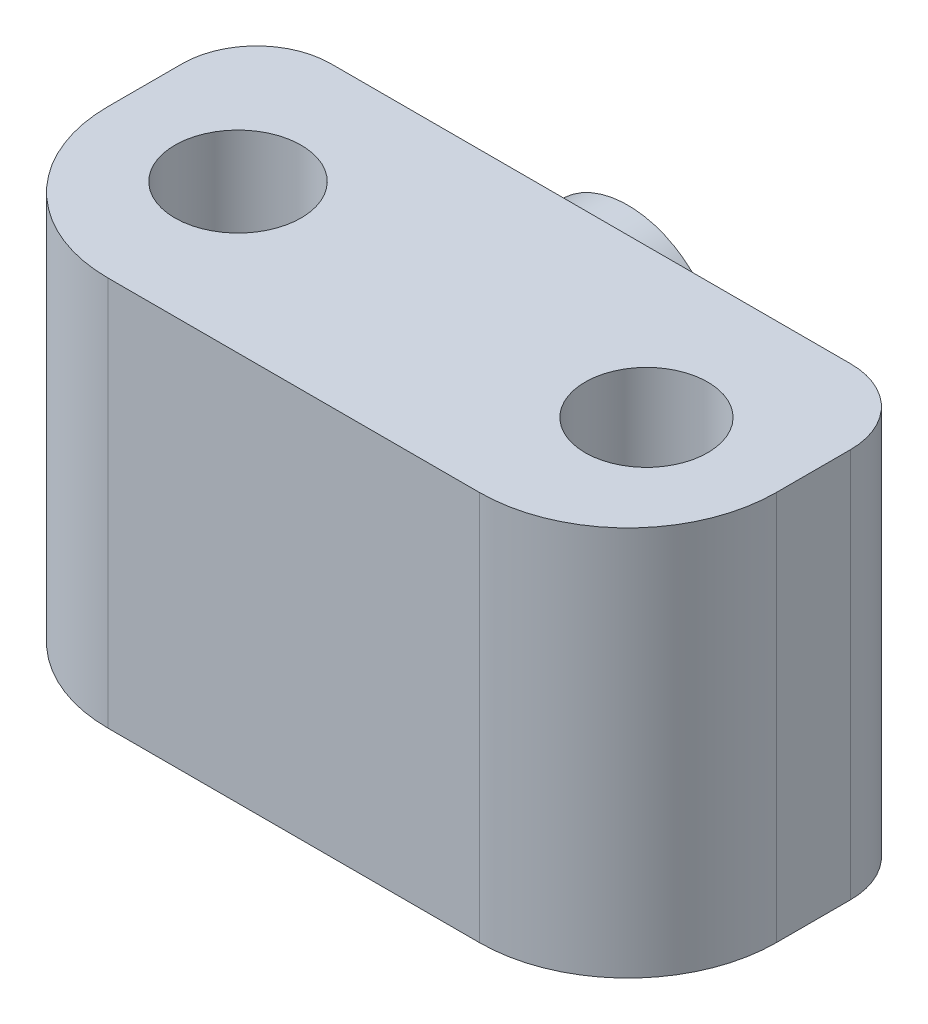
SolidWorks part; units mm, degrees
ref_plane "前视基准面" through (0, 0, 0) normal (0, 0, 1) x (1, 0, 0)
ref_plane "上视基准面" through (0, 0, 0) normal (0, 1, 0) x (1, 0, 0)
ref_plane "右视基准面" through (0, 0, 0) normal (1, 0, 0) x (0, 0, -1)
sketch "草图1" plane through (0, 0, 0) normal (0, 0, 1) x (1, 0, 0)
  line L1 (-9, 6.25) -> (9, 6.25)
  line L2 (-9, 6.25) -> (-9, -6.25)
  line L3 (-9, -6.25) -> (9, -6.25)
  line L4 (9, 6.25) -> (9, -6.25)
  line L5 (-9, 6.25) -> (9, -6.25) construction
  line L6 (-9, -6.25) -> (9, 6.25) construction
  point P0 (0, 0)
  dimension "D2" = 18
  dimension "D3" = 12.5
extrude "凸台-拉伸1" add sketch "草图1" along normal blind 8
sketch "草图2" plane through (0, 0, 0) normal (0, 0, -1) x (-1, 0, 0)
  line L0 (0, 1.45) -> (0, 0) construction
  circle A1 centre (0, 1.45) radius 1.625
  dimension "D1" = 1.45
  dimension "D2" = 3.25
extrude "切除-拉伸1" cut sketch "草图2" against normal mid plane 5
sketch "草图3" plane through (0, 0, 0) normal (0, 0, -1) x (-1, 0, 0)
  circle A3 centre (0, 1.45) radius 2.5
  circle A4 centre (0, 1.45) radius 1.625
  dimension "D1" = 3.25
  dimension "D2" = 5
extrude "凸台-拉伸2" add sketch "草图3" along normal blind 1
sketch "草图4" plane through (0, 6.25, 0) normal (0, 1, 0) x (1, 0, 0)
  line L0 (-9, -4) -> (9, -4) construction
  line L1 (-9, -8) -> (-9, 0) construction
  line L2 (9, -8) -> (9, 0) construction
  circle A0 centre (-5.5, -4) radius 1.25
  point P6 (-5.5, -4)
  dimension "D2" = 2.5
  dimension "D1" = 3.5
extrude "切除-拉伸2" cut sketch "草图4" against normal blind 25
mirror "镜向1" about plane through (0, 0, 0) normal (1, 0, 0) of "切除-拉伸2"
fillet "圆角1" radius 4 2 edges at (9, 0, 8) (-9, 0, 8)
fillet "圆角2" radius 2 2 edges at (9, 0, 0) (-9, 0, 0)
sketch "草图5" plane through (0, 6.25, 0) normal (0, 1, 0) x (1, 0, 0)
  line L2 (7, 0) -> (-7, 0)
  line L3 (-5, -8) -> (5, -8)
  line L4 (7, 0) -> (-7, 0)
  line L5 (-5, -8) -> (5, -8)
  line L8 (9, -4) -> (9, -2)
  line L9 (9, -4) -> (9, -2)
  line L10 (-9, -2) -> (-9, -4)
  line L11 (-9, -2) -> (-9, -4)
  arc A4 (5, -8) -> (9, -4) centre (5, -4) ccw
  arc A5 (9, -2) -> (7, 0) centre (7, -2) ccw
  arc A6 (-7, 0) -> (-9, -2) centre (-7, -2) ccw
  arc A7 (-9, -4) -> (-5, -8) centre (-5, -4) ccw
  arc A8 (5, -8) -> (9, -4) centre (5, -4) ccw
  arc A9 (9, -2) -> (7, 0) centre (7, -2) ccw
  arc A10 (-7, 0) -> (-9, -2) centre (-7, -2) ccw
  arc A11 (-9, -4) -> (-5, -8) centre (-5, -4) ccw
  dimension "D1" = 0
extrude "切除-拉伸3" cut sketch "草图5" against normal blind 2
sketch "草图6" plane through (0, 4.25, 0) normal (0, 1, 0) x (1, 0, 0)
  circle A0 centre (5.5, -4) radius 1.65
  circle A1 centre (-5.5, -4) radius 1.7
  dimension "D1" = 3.3
  dimension "D2" = 3.4
extrude "切除-拉伸4" cut sketch "草图6" against normal blind 8
